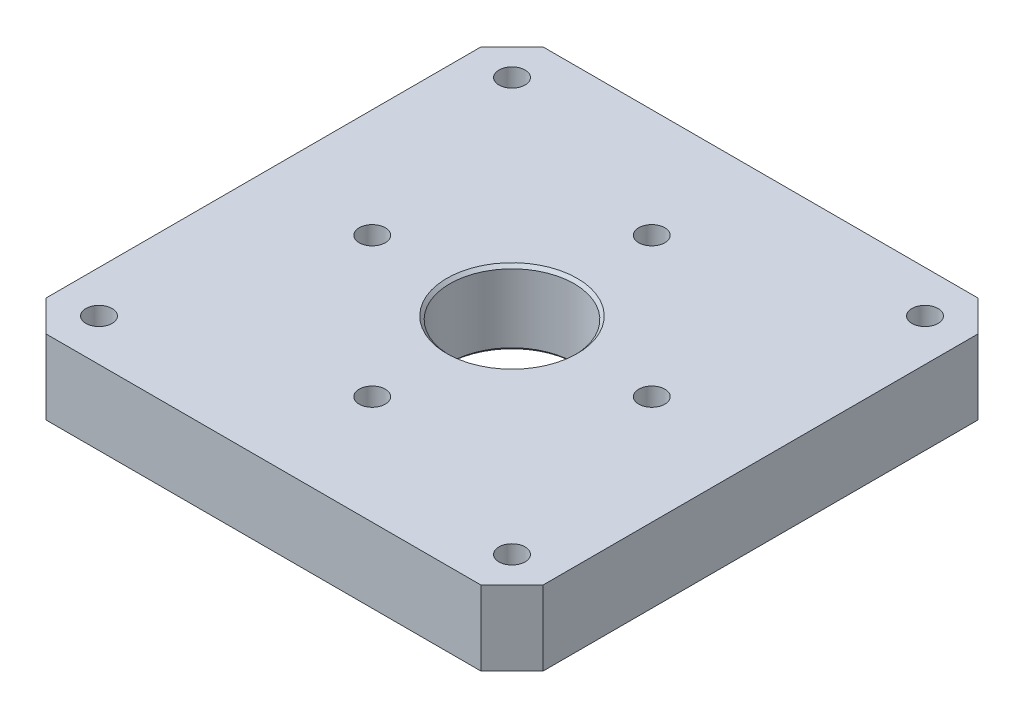
SolidWorks part; units mm, degrees
ref_plane "정면" through (0, 0, 0) normal (0, 0, 1) x (1, 0, 0)
ref_plane "윗면" through (0, 0, 0) normal (0, 1, 0) x (1, 0, 0)
ref_plane "우측면" through (0, 0, 0) normal (1, 0, 0) x (0, 0, -1)
sketch "스케치1" plane through (0, 0, 0) normal (0, 1, 0) x (1, 0, 0)
  line L0 (0, 75) -> (5, 80)
  line L1 (5, 0) -> (75, 0)
  line L2 (0, 5) -> (0, 75)
  line L3 (5, 80) -> (75, 80)
  line L4 (80, 5) -> (80, 75)
  line L5 (75, 80) -> (80, 75)
  line L6 (75, 0) -> (80, 5)
  line L7 (0, 5) -> (5, 0)
  line L8 (0, 80) -> (80, 0) construction
  line L9 (0, 0) -> (80, 80) construction
  circle A0 centre (40, 40) radius 47 construction
  circle A1 centre (40, 40) radius 22.5 construction
  point P0 (0, 0)
  point P1 (80, 80)
  point P2 (0, 80)
  point P3 (80, 0)
  point P19 (6.766, 73.234)
  point P20 (40, 62.5)
  point P21 (73.234, 73.234)
  point P22 (6.766, 6.766)
  point P23 (73.234, 6.766)
  point P25 (17.5, 40)
  point P26 (62.5, 40)
  point P27 (40, 17.5)
  dimension "D3" = 94
  dimension "D4" = 45
  dimension "D1" = 80
  dimension "D2" = 80
extrude "보스-돌출1" add sketch "스케치1" along normal blind 12
sketch "스케치4" plane through (0, 12, 0) normal (0, 1, 0) x (1, 0, 0)
  point P0 (6.766, 73.234)
  point P3 (40, 62.5)
  point P6 (73.234, 73.234)
  point P9 (62.5, 40)
  point P12 (40, 17.5)
  point P15 (17.5, 40)
  point P18 (6.766, 6.766)
  point P21 (73.234, 6.766)
hole_wizard "M5 나사 구멍1" positions "스케치4" profile "스케치3" tap size "M5" standard "ISO" end condition through all
sketch "스케치3" plane through (6.766, 12, -73.234) normal (1, 0, 0) x (0, 0, 1)
  line L0 (0, 0) -> (0, 12)
  line L1 (0, 12) -> (2.1, 12)
  line L2 (2.1, 12) -> (2.1, 0)
  line L5 (2.1, 0) -> (0, 0)
  line L11 (0, -6.35) -> (0, 107.95) construction
  dimension "관통 탭 드릴 지름" = 4.2
  dimension "관통 탭 드릴 깊이" = 12
cosmetic thread "구멍 나사산1" parameters "D2"=5
cosmetic thread "구멍 나사산2" parameters "D2"=5
cosmetic thread "구멍 나사산3" parameters "D2"=5
cosmetic thread "구멍 나사산4" parameters "D2"=5
cosmetic thread "구멍 나사산5" parameters "D2"=5
cosmetic thread "구멍 나사산6" parameters "D2"=5
cosmetic thread "구멍 나사산7" parameters "D2"=5
cosmetic thread "구멍 나사산8" parameters "D2"=5
sketch "스케치5" plane through (0, 12, 0) normal (0, 1, 0) x (1, 0, 0)
  line L0 (40, 62.5) -> (40, 17.5) construction
  line L1 (62.5, 40) -> (17.5, 40) construction
  circle A0 centre (40, 40) radius 10
  dimension "D1" = 20
extrude "컷-돌출1" cut sketch "스케치5" against normal through all
chamfer "모따기1" distance 0.5 angle 45 2 edges at (40, 0, -30) (40, 12, -30)
